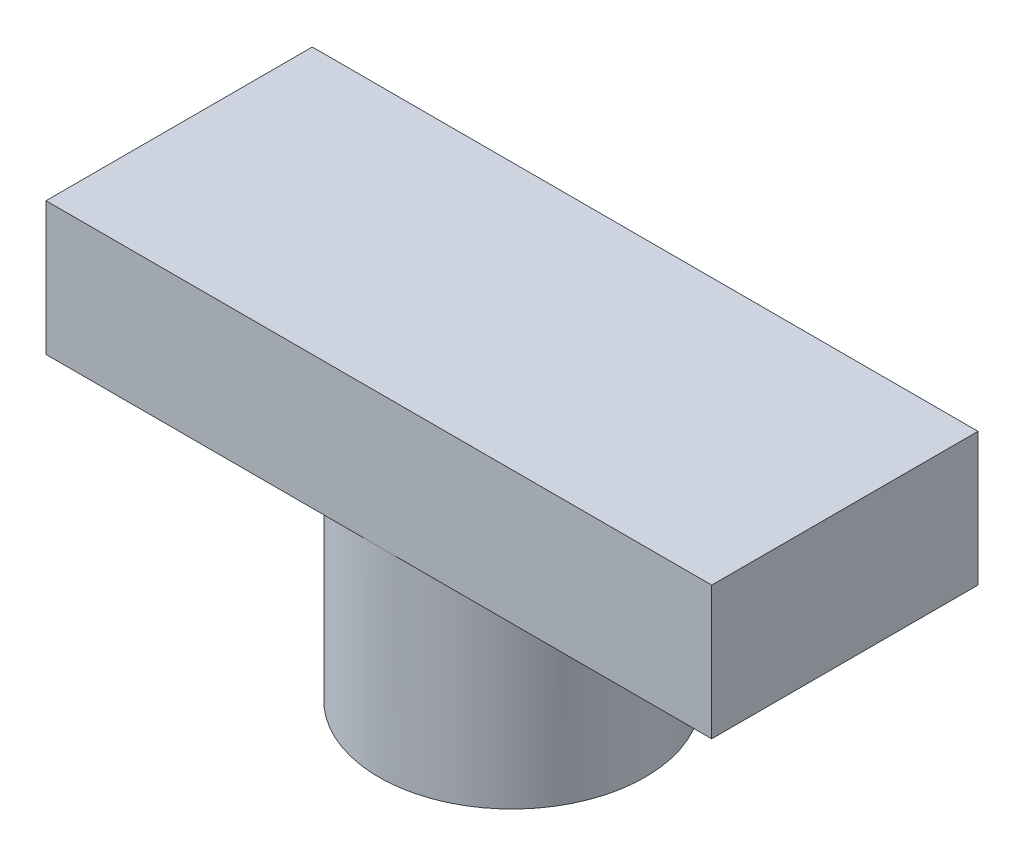
SolidWorks part; units mm, degrees
ref_plane "Front Plane" through (0, 0, 0) normal (0, 0, 1) x (1, 0, 0)
ref_plane "Top Plane" through (0, 0, 0) normal (0, 1, 0) x (1, 0, 0)
ref_plane "Right Plane" through (0, 0, 0) normal (1, 0, 0) x (0, 0, -1)
sketch "Sketch2" plane through (0, 0, 0) normal (0, 1, 0) x (1, 0, 0)
  line L1 (0, 0) -> (10, 0)
  line L2 (0, 0) -> (0, 4)
  line L3 (0, 4) -> (10, 4)
  line L4 (10, 0) -> (10, 4)
  dimension "D1" = 4
  dimension "D2" = 10
extrude "Boss-Extrude2" add sketch "Sketch2" along normal blind 2
sketch "Sketch3" plane through (0, 0, 0) normal (0, -1, 0) x (1, 0, 0)
  line L0 (0, -4) -> (0, 0) construction
  line L1 (10, -4) -> (0, -4) construction
  circle A0 centre (5, -2) radius 2
  point P2 (0, 0)
  point P5 (0, -2)
  point P6 (0, 0)
  point P9 (5, -4)
  dimension "D1" = 4
extrude "Boss-Extrude3" add sketch "Sketch3" along normal blind 3
